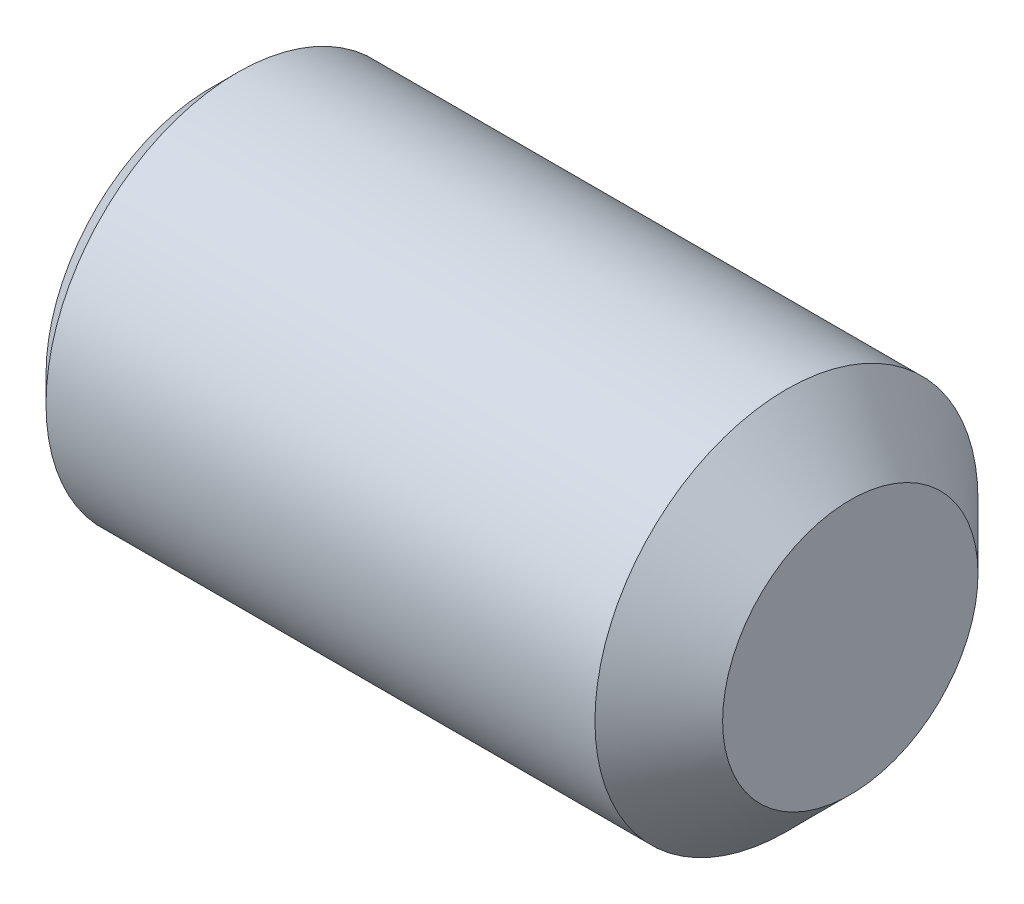
SolidWorks part; units mm, degrees
revolve "基体-旋转" add sketch "草图1" angle 360 about L6
sketch "草图1" plane through (0, 0, 0) normal (0, 0, 1) x (1, 0, 0)
  line L0 (0, 0) -> (10, 0)
  line L1 (10, 0) -> (10, 2)
  line L2 (10, 2) -> (9, 3)
  line L3 (9, 3) -> (0.402, 3)
  line L4 (0.402, 3) -> (0, 2.598)
  line L5 (0, 2.598) -> (0, 0)
  line L6 (-0.2778, 0) -> (5.1995, 0) construction
  dimension "l" = 10
  dimension "df" = 5.196
  dimension "d" = 6
  dimension "dp" = 4
  dimension "D1" = 45
  dimension "D2" = 45
cosmetic thread "装饰螺纹线1" parameters "df"=5.196
extrude "切除-拉伸1" cut sketch "草图2" against normal blind 2
sketch "草图2" plane through (0, 0, 0) normal (-1, 0, 0) x (0, 0, 1)
  line L1 (-0.86, -1.4896) -> (0.86, -1.4896)
  line L2 (0.86, -1.4896) -> (1.72, 0)
  line L3 (1.72, 0) -> (0.86, 1.4896)
  line L4 (0.86, 1.4896) -> (-0.86, 1.4896)
  line L5 (-0.86, 1.4896) -> (-1.72, 0)
  line L6 (-1.72, 0) -> (-0.86, -1.4896)
  circle A0 centre (0, 0) radius 1.4896 construction
  dimension "e" = 3.44
material "AISI 304"
ref_plane "前视" through (0, 0, 0) normal (0, 0, 1) x (1, 0, 0)
ref_plane "上视" through (0, 0, 0) normal (0, 1, 0) x (1, 0, 0)
ref_plane "右视" through (0, 0, 0) normal (1, 0, 0) x (0, 0, -1)
sketch "尺寸草图" plane through (0, 0, 0) normal (0, 0, 1) x (1, 0, 0)
  line L0 (0, 0) -> (10, 0)
  point P3 (2, 0)
  point P4 (9, 0)
  point P5 (6, 0)
  point P6 (5.196, 0)
  point P7 (6, 0)
  point P8 (6.56, 0)
  dimension "l" = 10
  dimension "df" = 5.196
  dimension "d" = 6
  dimension "dp" = 4
  dimension "P" = 1
  dimension "t" = 2
  dimension "e" = 3.44
sketch "草图4" plane through (0, 0, 0) normal (0, 0, 1) x (1, 0, 0)
  line L0 (-0.2778, 0) -> (1.1933, 0) construction
  line L2 (-0.2778, 0) -> (5.1995, 0) construction
  line L3 (2, 1.4896) -> (2.86, 0)
  line L4 (2.86, 0) -> (2, 0)
  line L5 (2, 0) -> (2, 1.4896)
  line L6 (2, 1.4896) -> (0, 1.4896) construction
  dimension "D1" = 60
  dimension "D2" = 2
revolve "切除-旋转2" cut sketch "草图4" angle 360 about L0
sketch "草图5" plane through (0, 0, 0) normal (0, 0, 1) x (1, 0, 0)
  line L0 (0.402, 3) -> (1.402, 3)
  line L1 (9, 3) -> (0.402, 3) construction
  line L2 (1.402, 3) -> (0.8966, 2.134)
  line L3 (0.8966, 2.134) -> (0.402, 3)
  line L5 (5.1995, 0) -> (3.6008, 0) construction
  line L6 (-0.2778, 0) -> (5.1995, 0) construction
  line L7 (0.402, 3) -> (0, 2.598) construction
  dimension "P" = 1
  dimension "D1" = 0.866
  dimension "D2" = 60
revolve "切除-旋转3" [suppressed] cut sketch "草图5" angle 360 about L5
pattern_linear "阵列(线性)1" [suppressed] count 10
equation "\"l@草图1\"=\"l@尺寸草图\""
equation "\"d@草图1\"=\"d@尺寸草图\""
equation "\"df@草图1\" = \"df@尺寸草图\""
equation "\"dp@草图1\" = \"dp@尺寸草图\""
equation "\"e@草图2\" = \"e@尺寸草图\""
equation "\"t@切除-拉伸1\" = \"t@尺寸草图\""
equation "\"P@草图5\" = \"P@尺寸草图\""
equation "\"D1@草图5\" = \"P@尺寸草图\"*0.866"
equation "\"P@阵列(线性)1\" = \"P@尺寸草图\""
equation "\"D1@阵列(线性)1\" = \"l@尺寸草图\"/\"P@尺寸草图\""
equation "\"df@装饰螺纹线1\"=\"df@尺寸草图\""
equation "\"D2@草图4\" = \"t@尺寸草图\""
